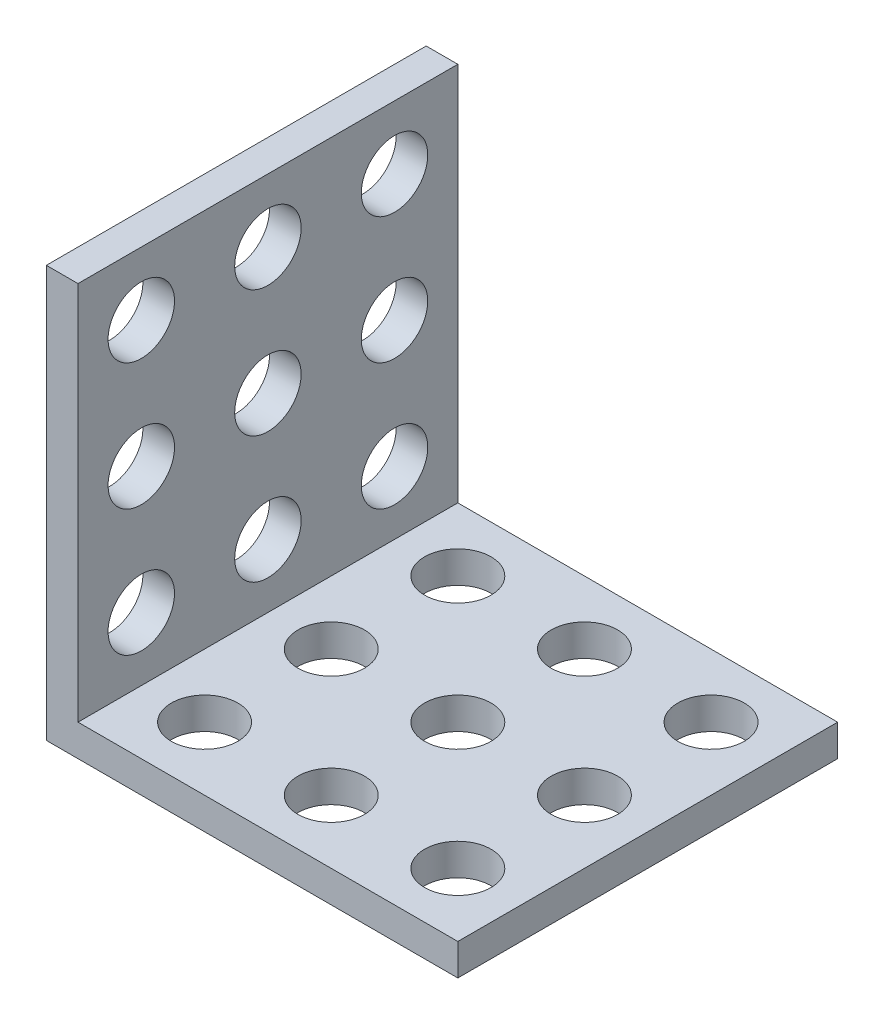
SolidWorks part; units mm, degrees
material "Alliage 6061"
ref_plane "Face" through (0, 0, 0) normal (0, 0, 1) x (1, 0, 0)
ref_plane "Dessus" through (0, 0, 0) normal (0, 1, 0) x (1, 0, 0)
ref_plane "Droite" through (0, 0, 0) normal (1, 0, 0) x (0, 0, -1)
sketch "Esquisse1" plane through (0, 0, 0) normal (0, 0, 1) x (1, 0, 0)
  line L0 (0, 24) -> (0, 0)
  line L1 (0, 0) -> (24, 0)
  dimension "D1" = 24
extrude "Extru.-Mince1" add sketch "Esquisse1" along normal blind 24 thin
sketch "Esquisse2" plane through (0, 0, 0) normal (0, 1, 0) x (1, 0, 0)
  line L0 (0, -24) -> (24, -24) construction
  line L1 (0, -24) -> (0, 0) construction
  circle A0 centre (4, -20) radius 2.1
  dimension "D1" = 4.2
  dimension "D2" = 4
  dimension "D3" = 4
extrude "Enlèv. mat.-Extru.1" cut sketch "Esquisse2" against normal through all
pattern_linear "Répétition linéaire1" count 3 spacing 8 along (1, 0, 0) count 3 spacing 8 along (0, 0, -1) of "Enlèv. mat.-Extru.1"
sketch "Esquisse3" plane through (0, 0, 0) normal (1, 0, 0) x (0, 0, -1)
  line L0 (-24, 0) -> (0, 0) construction
  line L4 (-24, 24) -> (-24, 0) construction
  circle A0 centre (-20, 4) radius 2.1
  dimension "D1" = 4.2
  dimension "D2" = 4
  dimension "D3" = 4
extrude "Enlèv. mat.-Extru.2" cut sketch "Esquisse3" against normal through all
pattern_linear "Répétition linéaire2" count 3 spacing 8 along (0, 1, 0) count 3 spacing 8 along (0, 0, -1) of "Enlèv. mat.-Extru.2"
